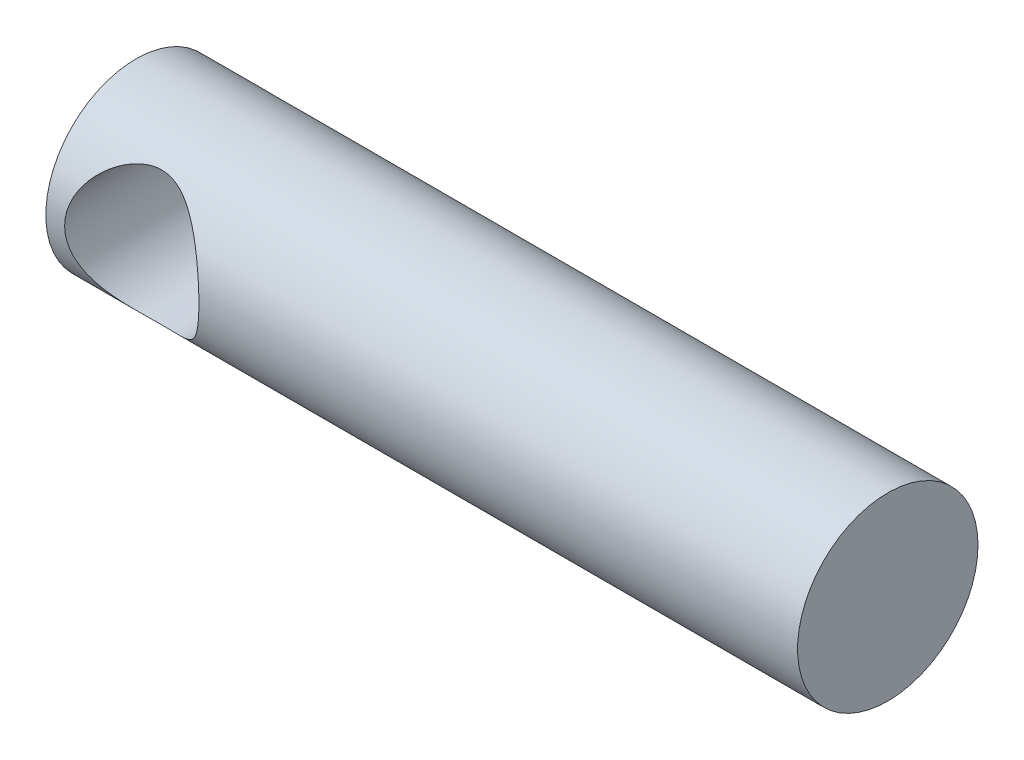
SolidWorks part; units mm, degrees
ref_plane "Front Plane" through (0, 0, 0) normal (0, 0, 1) x (1, 0, 0)
ref_plane "Top Plane" through (0, 0, 0) normal (0, 1, 0) x (1, 0, 0)
ref_plane "Right Plane" through (0, 0, 0) normal (1, 0, 0) x (0, 0, -1)
sketch "Sketch1" plane through (0, 0, 0) normal (1, 0, 0) x (0, 0, -1)
  circle A0 centre (0, 0) radius 10.668
  dimension "D1" = 21.336
extrude "Boss-Extrude1" add sketch "Sketch1" along normal blind 88.9
sketch "Sketch2" plane through (0, 0, 0) normal (0, 0, 1) x (1, 0, 0)
  circle A0 centre (10.16, 0) radius 7.9375
  point P2 (8.9008, 0)
  point P3 (0, 0)
  point P4 (8.9667, 0)
  dimension "D1" = 15.875
  dimension "D2" = 10.16
extrude "Cut-Extrude2" cut sketch "Sketch2" against normal through all both and the other way through all contours A0
